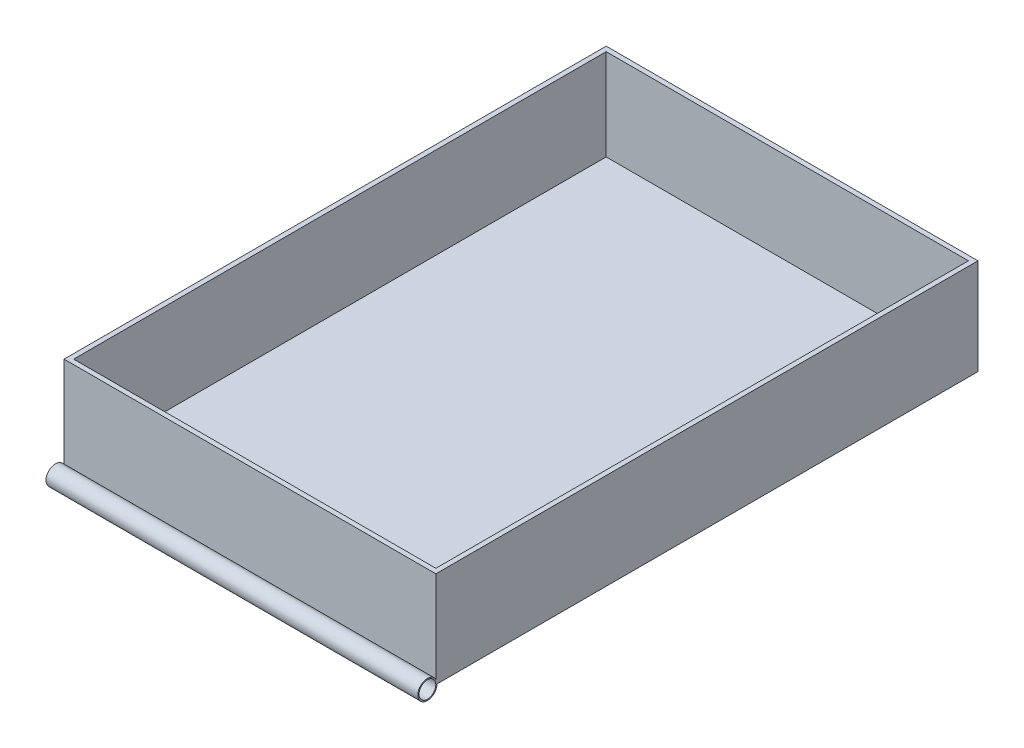
SolidWorks part; units mm, degrees
ref_plane "Front Plane" through (0, 0, 0) normal (0, 0, 1) x (1, 0, 0)
ref_plane "Top Plane" through (0, 0, 0) normal (0, 1, 0) x (1, 0, 0)
ref_plane "Right Plane" through (0, 0, 0) normal (1, 0, 0) x (0, 0, -1)
sketch "Sketch1" plane through (0, 0, 0) normal (0, 1, 0) x (1, 0, 0)
  line L1 (-387.5, 565) -> (387.5, 565)
  line L2 (-387.5, 565) -> (-387.5, -565)
  line L3 (-387.5, -565) -> (387.5, -565)
  line L4 (387.5, 565) -> (387.5, -565)
  line L5 (-387.5, 565) -> (387.5, -565) construction
  line L6 (-387.5, -565) -> (387.5, 565) construction
  point P0 (0, 0)
  dimension "D1" = 775
  dimension "D2" = 1130
extrude "Boss-Extrude1" add sketch "Sketch1" along normal blind 200
shell "Shell1" thickness 10
sketch "Sketch4" plane through (387.5, 0, 0) normal (1, 0, 0) x (0, 0, -1)
  line L1 (-565, 0) -> (-582.6669, 0) construction
  circle A0 centre (-582.6669, 0) radius 20
  point P2 (0, 0)
  point P5 (0, 0)
extrude "Boss-Extrude3" add sketch "Sketch4" against normal blind 775
sketch "Sketch5" plane through (387.5, 0, 0) normal (1, 0, 0) x (0, 0, -1)
  circle A0 centre (-582.6669, 0) radius 17.5
extrude "Cut-Extrude2" cut sketch "Sketch5" against normal blind 1280
ref_plane "Plane1" through (0, 0, 0) normal (0, 0, 1) x (1, 0, 0)
